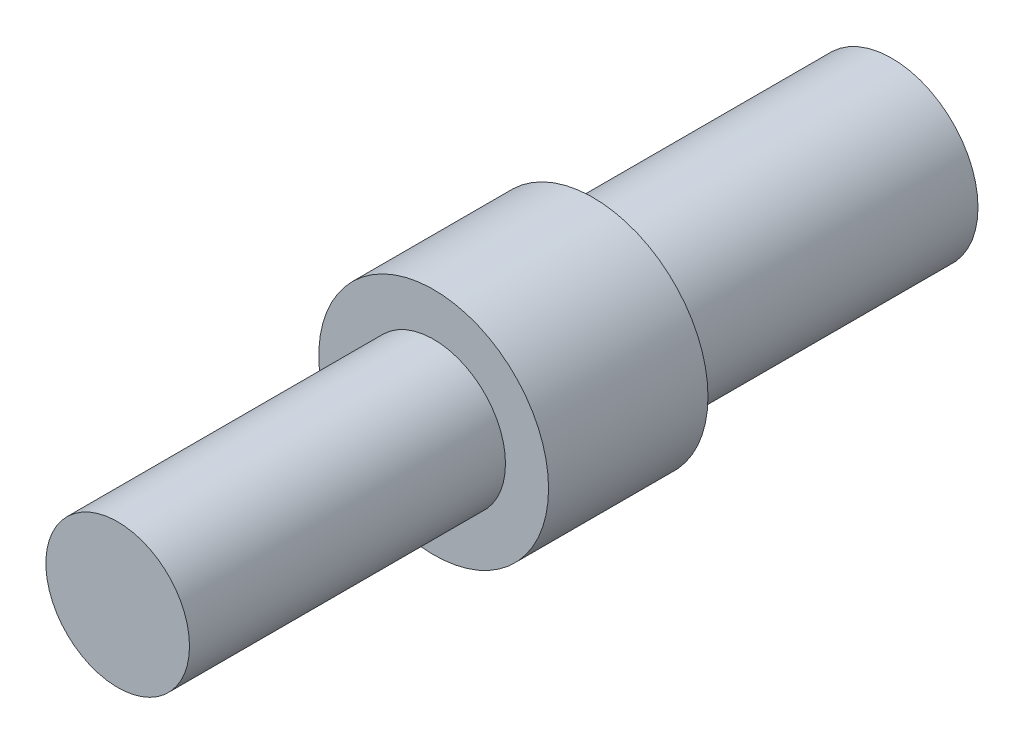
SolidWorks part; units mm, degrees
ref_plane "Front Plane" through (0, 0, 0) normal (0, 0, 1) x (1, 0, 0)
ref_plane "Top Plane" through (0, 0, 0) normal (0, 1, 0) x (1, 0, 0)
ref_plane "Right Plane" through (0, 0, 0) normal (1, 0, 0) x (0, 0, -1)
sketch "S01 - 12 mm bearing journal" plane through (0, 0, 0) normal (0, 0, 1) x (1, 0, 0)
  circle A0 centre (0, 0) radius 6
  dimension "D1" = 12
extrude "01 - 12 mm bearing journal" add sketch "S01 - 12 mm bearing journal" along normal blind 20.8
sketch "S02 - Grounded journal shoulder" plane through (0, 0, 0) normal (0, 0, 1) x (1, 0, 0)
  circle A0 centre (0, 0) radius 8
  dimension "D1" = 16
extrude "02 - Grounded journal shoulder" add sketch "S02 - Grounded journal shoulder" along normal blind 11.1 from offset 20.8
sketch "S03 - M10 threaded bridge stem" plane through (0, 0, 0) normal (0, 0, 1) x (1, 0, 0)
  circle A0 centre (0, 0) radius 5
  dimension "D1" = 10
extrude "03 - M10 threaded bridge stem" add sketch "S03 - M10 threaded bridge stem" along normal blind 22 from offset 31.9
sketch "S04 - M5 tapped end - nominal thread envelope" plane through (0, 0, 0) normal (0, 0, 1) x (1, 0, 0)
  circle A0 centre (0, 0) radius 2.53
  dimension "D1" = 5.06
extrude "04 - M5 tapped end - nominal thread envelope" cut sketch "S04 - M5 tapped end - nominal thread envelope" along normal blind 9.1 from offset 0.1
